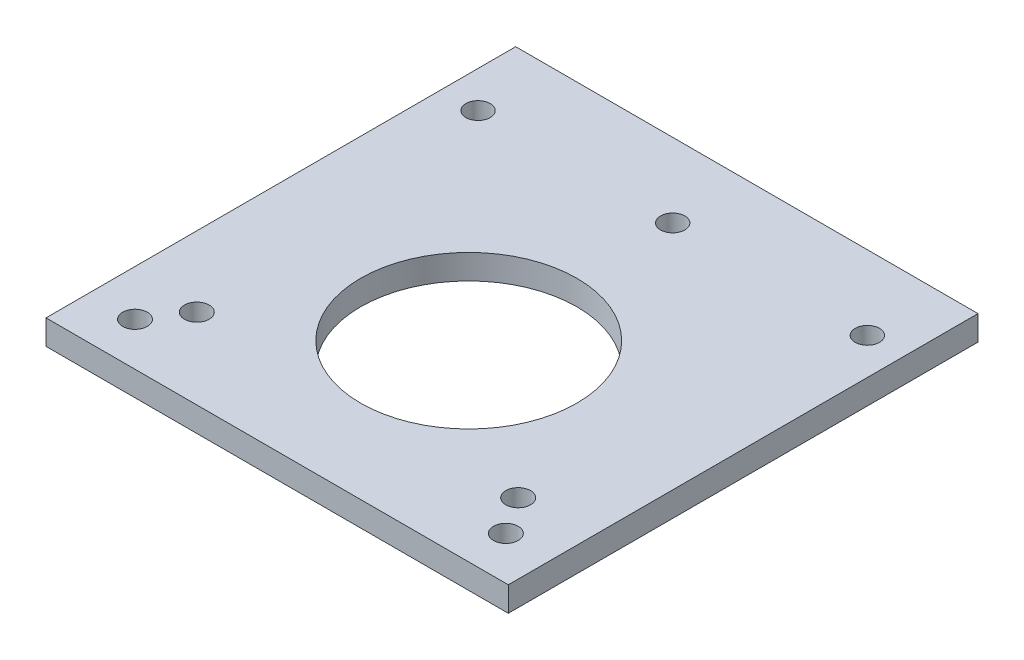
SolidWorks part; units mm, degrees
material "6061 Alloy"
ref_plane "Front Plane" through (0, 0, 0) normal (0, 0, 1) x (1, 0, 0)
ref_plane "Top Plane" through (0, 0, 0) normal (0, 1, 0) x (1, 0, 0)
ref_plane "Right Plane" through (0, 0, 0) normal (1, 0, 0) x (0, 0, -1)
sketch "Sketch2" plane through (0, 0, 0) normal (0, 1, 0) x (1, 0, 0)
  line L0 (0, 0) -> (0, 35.56) construction
  line L1 (-47.5, -60.96) -> (-47.5, 35.56)
  line L2 (47.5, -60.96) -> (47.5, 35.56)
  line L3 (-47.5, 35.56) -> (47.5, 35.56)
  line L4 (-47.5, -60.96) -> (47.5, -60.96)
  point P3 (47.5, -12.7)
  point P5 (0, 35.56)
  point P12 (0, -60.96)
  dimension "D1" = 96.52
  dimension "D2" = 95
  dimension "D3" = 12.7
extrude "Boss-Extrude3" add sketch "Sketch2" along normal blind 5.08
sketch "Sketch3" plane through (0, 5.08, 0) normal (0, 1, 0) x (1, 0, 0)
  line L0 (47.5, 35.56) -> (-47.5, 35.56) construction
  circle A1 centre (0, -21.59) radius 22.225
  dimension "D2" = 44.45
  dimension "D3" = 57.15
extrude "Cut-Extrude1" cut sketch "Sketch3" against normal through all
sketch "Sketch4" plane through (0, 5.08, 0) normal (0, 1, 0) x (1, 0, 0)
  line L0 (47.5, 35.56) -> (-47.5, 35.56) construction
  line L1 (0, 35.56) -> (0, 55.3884) construction
  point P0 (-40, 20.32)
  point P7 (40, 20.32)
  point P8 (0, 20.32)
  point P10 (0, 20.32)
  dimension "D1" = 15.24
  dimension "D2" = 80
hole_wizard "M6x1.0 Tapped Hole1" positions "Sketch4" profile "Sketch6" tap size "M6x1.0" standard "ANSI Metric"
sketch "Sketch6" plane through (-40, 5.08, -20.32) normal (1, 0, 0) x (0, 0, 1)
  line L0 (0, 0) -> (0, 6.5822)
  line L1 (0, 6.5822) -> (2.5, 5.08)
  line L2 (2.5, 5.08) -> (2.5, 0)
  line L5 (2.5, 0) -> (0, 0)
  line L10 (0, 6.5822) -> (-2.5, 5.08) construction
  line L11 (0, -6.35) -> (0, 107.95) construction
  dimension "Tap Drill Dia." = 5
  dimension "Tap Drill Depth" = 5.08
  dimension "Drill Angle" = 118
sketch "Sketch7" plane through (0, 5.08, 0) normal (0, 1, 0) x (1, 0, 0)
  line L0 (0, 0) -> (0, -60.96) construction
  line L1 (-47.5, -60.96) -> (47.5, -60.96) construction
  circle A0 centre (-33.02, -44.45) radius 2.54
  circle A1 centre (33.02, -44.45) radius 2.54
  circle A2 centre (-38.1, -52.07) radius 2.54
  circle A3 centre (38.1, -52.07) radius 2.54
  dimension "D3" = 5.08
  dimension "D4" = 5.08
  dimension "D1" = 44.45
  dimension "D2" = 33.02
  dimension "D5" = 38.1
  dimension "D6" = 7.62
extrude "Cut-Extrude2" cut sketch "Sketch7" against normal blind 7.62
